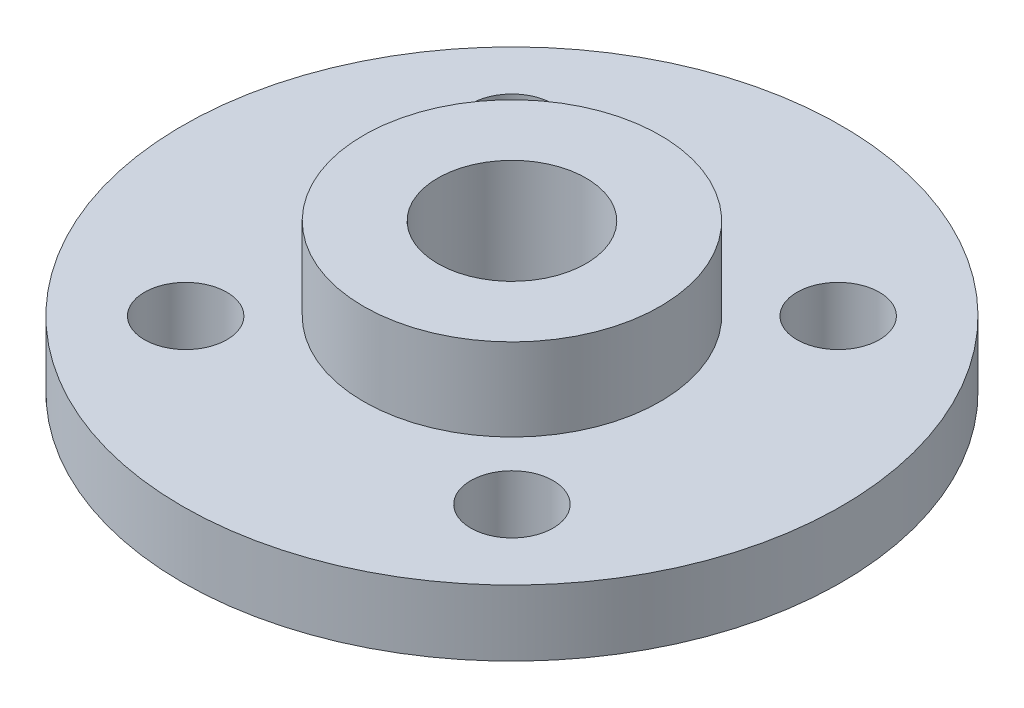
SolidWorks part; units mm, degrees
ref_plane "Front Plane" through (0, 0, 0) normal (0, 0, 1) x (1, 0, 0)
ref_plane "Top Plane" through (0, 0, 0) normal (0, 1, 0) x (1, 0, 0)
ref_plane "Right Plane" through (0, 0, 0) normal (1, 0, 0) x (0, 0, -1)
sketch "Sketch1" plane through (0, 0, 0) normal (0, 1, 0) x (1, 0, 0)
  line L0 (-4.9497, 4.9497) -> (4.9497, 4.9497) construction
  line L1 (4.9497, 4.9497) -> (4.9497, -4.9497) construction
  circle A0 centre (0, 0) radius 10
  circle A1 centre (-4.9497, 4.9497) radius 1.25
  circle A2 centre (4.9497, 4.9497) radius 1.25
  circle A3 centre (4.9497, -4.9497) radius 1.25
  circle A4 centre (-4.9497, -4.9497) radius 1.25
  circle A5 centre (0, 0) radius 7 construction
  circle A6 centre (0, 0) radius 1.5
  dimension "D1" = 20
  dimension "D2" = 2.5
  dimension "D3" = 3
  dimension "D4" = 14
extrude "Boss-Extrude1" add sketch "Sketch1" along normal blind 2
cosmetic thread "Cosmetic Thread1" parameters "D2"=3
cosmetic thread "Cosmetic Thread2" parameters "D2"=3
cosmetic thread "Cosmetic Thread3" parameters "D2"=3
cosmetic thread "Cosmetic Thread4" parameters "D2"=3
sketch "Sketch2" plane through (0, 2, 0) normal (0, 1, 0) x (1, 0, 0)
  circle A0 centre (0, 0) radius 4.5
  circle A1 centre (0, 0) radius 1.5 construction
  circle A2 centre (0, 0) radius 1.5
  dimension "D1" = 9
extrude "Boss-Extrude2" add sketch "Sketch2" along normal blind 2.5
sketch "Sketch3" plane through (0, 4.5, 0) normal (0, 1, 0) x (1, 0, 0)
  circle A0 centre (0, 0) radius 2.25
  dimension "D1" = 4.5
extrude "Cut-Extrude1" cut sketch "Sketch3" against normal blind 3.6
sketch "Sketch7" plane through (0, 4.5, 0) normal (0, 1, 0) x (1, 0, 0)
  circle A0 centre (0, 0.1027) radius 2.8429
extrude "Cut-Extrude2" [suppressed] cut sketch "Sketch7" against normal up to surface (3.6 mm away)
chamfer "Chamfer1" [suppressed] distance 0.1 angle 45
